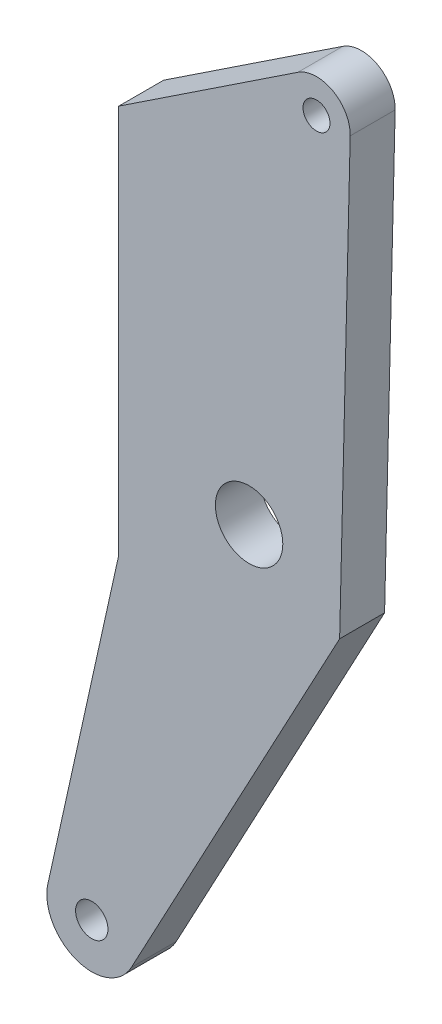
SolidWorks part; units mm, degrees
ref_plane "Front Plane" through (0, 0, 0) normal (0, 0, 1) x (1, 0, 0)
ref_plane "Top Plane" through (0, 0, 0) normal (0, 1, 0) x (1, 0, 0)
ref_plane "Right Plane" through (0, 0, 0) normal (1, 0, 0) x (0, 0, -1)
sketch "Sketch1" plane through (0, 0, 0) normal (0, 0, 1) x (1, 0, 0)
  line L6 (0, 0) -> (50.8, 0) construction
  line L7 (35.0174, 51.9098) -> (36.5111, 114.1858)
  line L8 (22.225, 59.4836) -> (0, 0) construction
  line L9 (-6.095, 1.7813) -> (3.81, 46.5296)
  line L10 (3.81, 46.5296) -> (3.81, 101.4738)
  line L11 (5.5972, -2.999) -> (35.0174, 51.9098)
  line L12 (3.81, 101.4738) -> (29.1166, 118.2682)
  circle A0 centre (0, 0) radius 2.286
  arc A1 (-6.095, 1.7813) -> (5.5972, -2.999) centre (0, 0) ccw
  circle A3 centre (31.75, 114.3) radius 1.905
  arc A5 (36.5111, 114.1858) -> (29.1166, 118.2682) centre (31.75, 114.3) ccw
  circle A6 centre (22.225, 59.4836) radius 4.7625
  dimension "D1" = 12.7
  dimension "D2" = 4.572
  dimension "D8" = 63.5
  dimension "D9" = 22.225
  dimension "D6" = 3.81
  dimension "D3" = 9.525
  dimension "D10" = 9.525
  dimension "D4" = 31.75
  dimension "D7" = 114.3
extrude "Boss-Extrude1" add sketch "Sketch1" along normal blind 6.35
sketch "Sketch2" plane through (3.81, 0, 0) normal (-1, 0, 0) x (0, 0, 1)
  line L0 (3.175, 89.8767) -> (3.175, 101.4738) construction
  line L1 (6.35, 101.4738) -> (0, 101.4738) construction
  line L2 (3.175, 46.5296) -> (3.175, 58.1267) construction
  line L3 (6.35, 46.5296) -> (0, 46.5296) construction
  circle A0 centre (3.175, 89.8767) radius 1.905
  circle A1 centre (3.175, 58.1267) radius 1.905
  point P8 (3.175, 88.9913)
  point P11 (0, 0)
  point P12 (3.175, 58.1267)
  dimension "D1" = 31.75
  dimension "D2" = 3.81
extrude "Cut-Extrude1" cut sketch "Sketch2" against normal blind 7.9375
